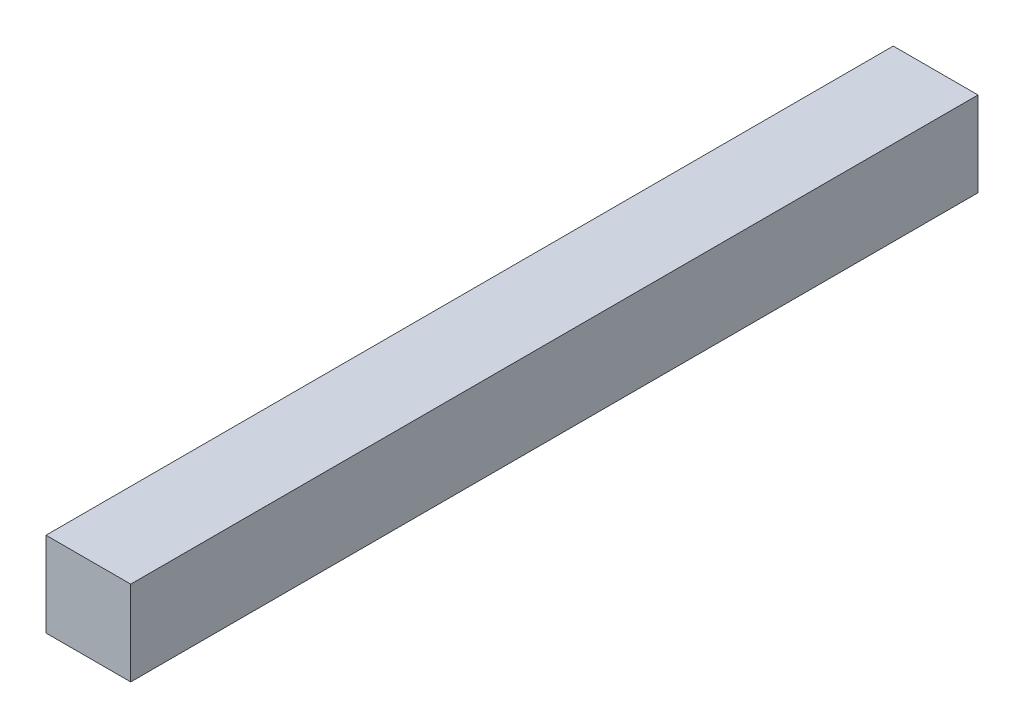
SolidWorks part; units mm, degrees
ref_plane "Front Plane" through (0, 0, 0) normal (0, 0, 1) x (1, 0, 0)
ref_plane "Top Plane" through (0, 0, 0) normal (0, 1, 0) x (1, 0, 0)
ref_plane "Right Plane" through (0, 0, 0) normal (1, 0, 0) x (0, 0, -1)
ref_point "Point1"
sketch "Sketch2" plane through (0, 0, 0) normal (0, 0, 1) x (1, 0, 0)
  line L1 (-5, 5) -> (5, 5)
  line L2 (-5, 5) -> (-5, -5)
  line L3 (-5, -5) -> (5, -5)
  line L4 (5, 5) -> (5, -5)
  line L5 (-5, 5) -> (5, -5) construction
  line L6 (-5, -5) -> (5, 5) construction
  point P0 (0, 0)
  dimension "D1" = 10
  dimension "D2" = 10
extrude "Boss-Extrude1" add sketch "Sketch2" against normal blind 100
ref_point "Point2"
